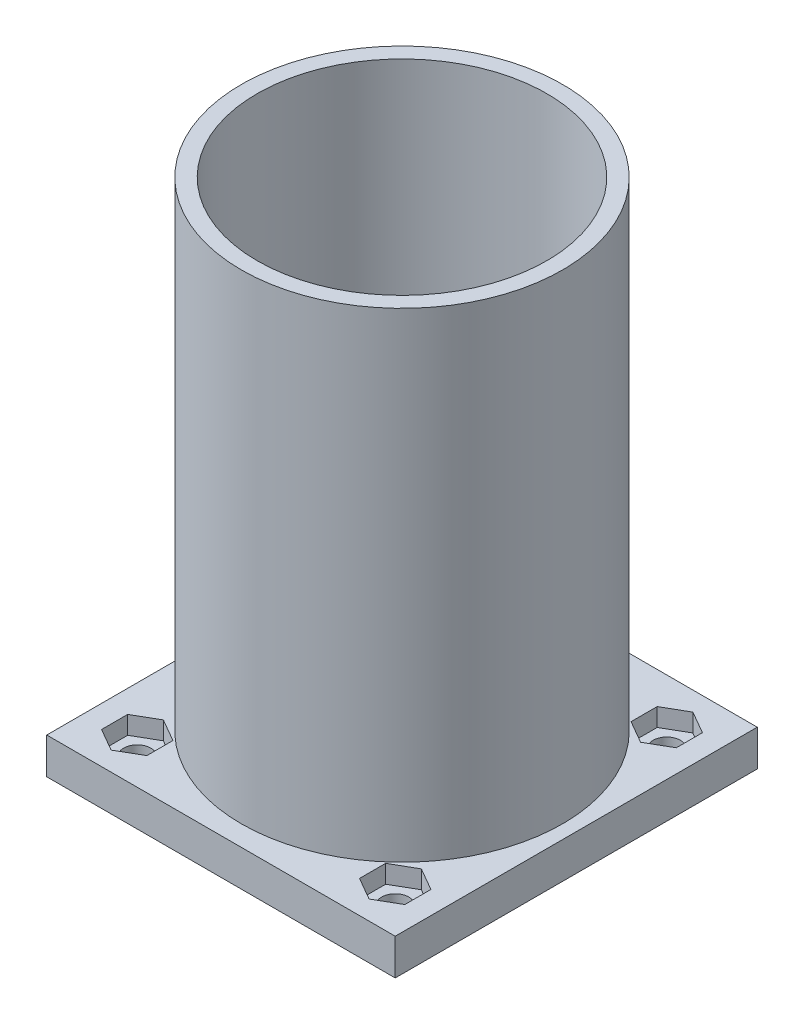
SolidWorks part; units mm, degrees
material "ABS"
ref_plane "Front Plane" through (0, 0, 0) normal (0, 0, 1) x (1, 0, 0)
ref_plane "Top Plane" through (0, 0, 0) normal (0, 1, 0) x (1, 0, 0)
ref_plane "Right Plane" through (0, 0, 0) normal (1, 0, 0) x (0, 0, -1)
sketch "Sketch1" plane through (0, 0, 0) normal (0, 1, 0) x (1, 0, 0)
  line L0 (0, 0) -> (50000, 0) construction
  line L1 (38.5, -40) -> (-38.5, -40)
  line L2 (38.5, -40) -> (38.5, 40)
  line L3 (38.5, 40) -> (-38.5, 40)
  line L4 (-38.5, -40) -> (-38.5, 40)
  line L5 (38.5, -40) -> (-38.5, 40) construction
  line L6 (38.5, 40) -> (-38.5, -40) construction
  line L7 (20, -12.5) -> (-20, -12.5)
  line L8 (20, -12.5) -> (20, 12.5)
  line L9 (20, 12.5) -> (-20, 12.5)
  line L10 (-20, -12.5) -> (-20, 12.5)
  line L11 (20, -12.5) -> (-20, 12.5) construction
  line L12 (20, 12.5) -> (-20, -12.5) construction
  circle A0 centre (-28.5014, 30) radius 3
  circle A1 centre (28.5, 30) radius 3
  circle A2 centre (28.5, -30) radius 3
  circle A3 centre (-28.5014, -30) radius 3
  point P0 (0, 0)
  point P10 (0, 0)
  dimension "D3" = 10
  dimension "D4" = 9.9986
  dimension "D5" = 10
  dimension "D6" = 10
  dimension "D7" = 6
  dimension "D8" = 6
  dimension "D1" = 77
  dimension "D2" = 80
  dimension "D9" = 40
  dimension "D10" = 25
extrude "Boss-Extrude1" add sketch "Sketch1" along normal mid plane 8
sketch "Sketch2" plane through (0, 0, 0) normal (0, 1, 0) x (1, 0, 0)
  line L0 (-33.5014, 32.8868) -> (-33.5014, 27.1132)
  line L1 (-23.5014, 27.1132) -> (-28.5014, 24.2265)
  line L2 (-33.5014, 27.1132) -> (-28.5014, 24.2265)
  line L3 (-33.5014, 32.8868) -> (-28.5014, 35.7735)
  line L4 (-23.5014, 32.8868) -> (-28.5014, 35.7735)
  line L5 (-23.5014, 30) -> (-23.5014, 32.8868)
  line L6 (-23.5014, 30) -> (-23.5014, 27.1132)
  line L7 (0, 0) -> (0, 50000) construction
  line L8 (-33.5014, 21.3397) -> (-33.542, 21.3163)
  line L9 (-1000, 0) -> (49000, 0) construction
  line L10 (23.5014, 30) -> (23.5014, 27.1132)
  line L11 (23.5014, 30) -> (23.5014, 32.8868)
  line L12 (23.5014, 32.8868) -> (28.5014, 35.7735)
  line L13 (33.5014, 32.8868) -> (28.5014, 35.7735)
  line L14 (33.5014, 27.1132) -> (28.5014, 24.2265)
  line L15 (23.5014, 27.1132) -> (28.5014, 24.2265)
  line L16 (33.5014, 32.8868) -> (33.5014, 27.1132)
  line L17 (33.5014, -32.8868) -> (33.5014, -27.1132)
  line L18 (23.5014, -27.1132) -> (28.5014, -24.2265)
  line L19 (33.5014, -27.1132) -> (28.5014, -24.2265)
  line L20 (33.5014, -32.8868) -> (28.5014, -35.7735)
  line L21 (23.5014, -32.8868) -> (28.5014, -35.7735)
  line L22 (23.5014, -30) -> (23.5014, -32.8868)
  line L23 (23.5014, -30) -> (23.5014, -27.1132)
  line L24 (-23.5014, -30) -> (-23.5014, -27.1132)
  line L25 (-23.5014, -30) -> (-23.5014, -32.8868)
  line L26 (-23.5014, -32.8868) -> (-28.5014, -35.7735)
  line L27 (-33.5014, -32.8868) -> (-28.5014, -35.7735)
  line L28 (-33.5014, -27.1132) -> (-28.5014, -24.2265)
  line L29 (-23.5014, -27.1132) -> (-28.5014, -24.2265)
  line L30 (-33.5014, -32.8868) -> (-33.5014, -27.1132)
  circle A0 centre (-28.5014, 30) radius 5 construction
  circle A1 centre (28.5, 30) radius 5 construction
  circle A2 centre (-28.5014, -30) radius 5 construction
  circle A3 centre (28.5, -30) radius 5 construction
  circle A4 centre (28.5014, 30) radius 5 construction
  circle A5 centre (28.5014, -30) radius 5 construction
  circle A6 centre (28.5, -30) radius 5 construction
  circle A7 centre (-28.5014, -30) radius 5 construction
  dimension "D1" = 10
  dimension "D2" = 10
  dimension "D3" = 10
  dimension "D4" = 10
  dimension "D5" = 120
  dimension "D6" = 120
  dimension "D7" = 120
  dimension "D8" = 120
extrude "Cut-Extrude1" cut sketch "Sketch2" along normal blind 10 contours L30 L27 L26 L25 L24 L29 L28 | L6 L5 L4 L3 L0 L2 L1 | L23 L22 L21 L20 L17 L19 L18 | L15 L14 L16 L13 L12 L11 L10
sketch "Sketch3" plane through (0, 0, 0) normal (0, 1, 0) x (1, 0, 0)
  circle A0 centre (0, 0) radius 35.5
  circle A1 centre (0, 0) radius 32
  dimension "D1" = 71
  dimension "D2" = 64
extrude "Boss-Extrude2" add sketch "Sketch3" along normal blind 110
sketch "Sketch5" plane through (0, 4, 0) normal (0, 1, 0) x (1, 0, 0)
  circle A0 centre (0, 0) radius 32
  dimension "D1" = 64
extrude "Boss-Extrude3" add sketch "Sketch5" along normal mid plane 10
